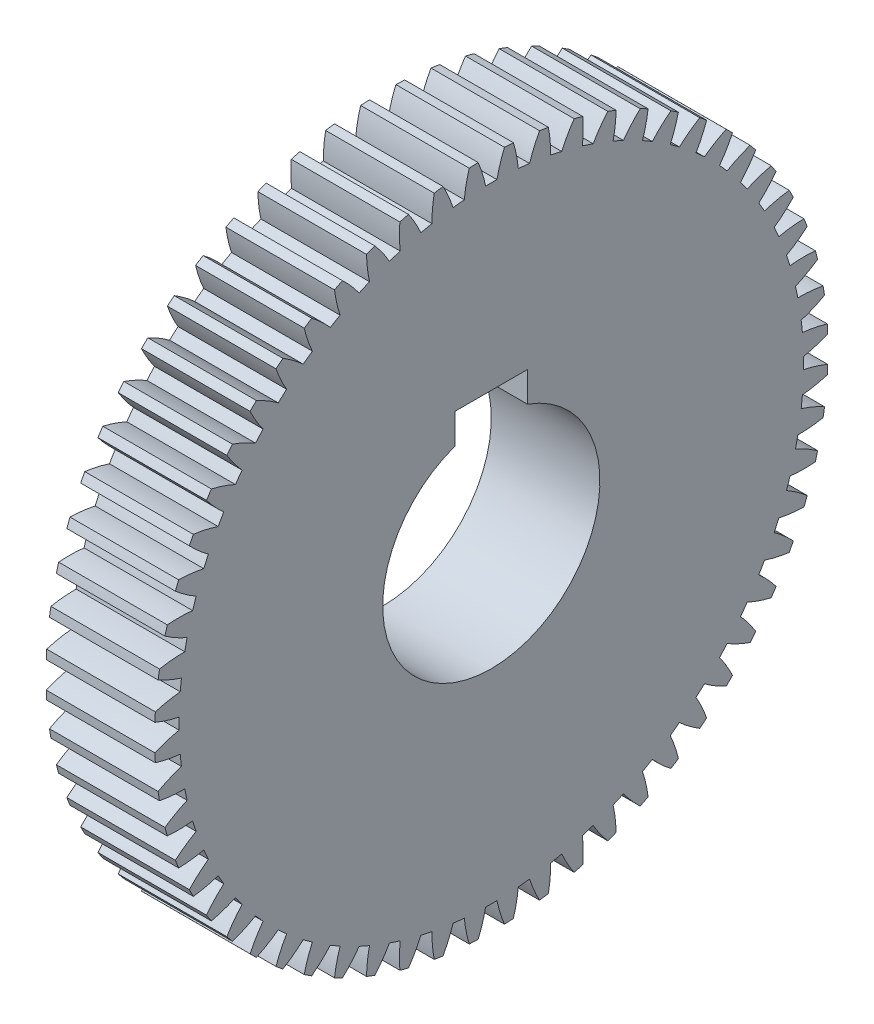
SolidWorks part; units mm, degrees
ref_plane "Plane1" through (0, 0, 0) normal (0, 0, 1) x (1, 0, 0)
ref_plane "Plane2" through (0, 0, 0) normal (0, 1, 0) x (1, 0, 0)
ref_plane "Plane3" through (0, 0, 0) normal (1, 0, 0) x (0, 0, -1)
sketch "HoldingSke" plane through (0, 0, 0) normal (0, 1, 0) x (1, 0, 0)
  line L0 (0, 0) -> (0.3333, -0.5774)
  line L1 (-15, 0) -> (100, 0) construction
  line L2 (0, 0) -> (-2.1039, 2.3779)
  line L3 (0, 0) -> (-11.863, 4.5341)
  line L4 (0, 0) -> (4.318, 7.479)
  line L5 (0, 0) -> (-46.8476, -17.4728)
  line L6 (0, 0) -> (-12.4344, -8.3896)
  line L7 (-2.1039, 2.3779) -> (8.6586, 51.2059)
  line L8 (-76.2, 54.61) -> (-72.9, 54.61)
  line L9 (-67.7845, 28.3722) -> (-49.3413, 33.142)
  line L10 (-76.2, 71.12) -> (104.1128, 71.12)
  line L11 (0, 0) -> (-15, 0)
  line L12 (-76.2, 101.6) -> (-76.147, 101.6)
  line L13 (24.9733, 27.94) -> (52.9518, 28.4284)
  line L14 (24.9733, 27.94) -> (24.9743, 27.94)
  line L15 (24.9733, 27.94) -> (100.4006, 29.5858)
  line L16 (-63.627, -1.5) -> (-12.827, -1.5)
  circle A0 centre (0, 0) radius 15
  circle A1 centre (0, 0) radius 37.5
  circle A2 centre (0, 0) radius 37.5
  circle A3 centre (0, 0) radius 15
  dimension "MHD" = 75
  dimension "Hub_dia" = 75
  dimension "Bore" = 30
  dimension "MBD" = 30
  dimension "Num_teeth" = 60
  dimension "Pitch" = 0.6667
  dimension "Overall_len" = 50
  dimension "Show_teeth" = 60
  dimension "Thickness" = 15
  dimension "OAL" = 50.0001
  dimension "T_dim" = 3.3
  dimension "Ap" = 14.5
  dimension "H" = 19.05
  dimension "Pitch_radius" = 180.3128
  dimension "Width" = 15
  dimension "Backlash" = 0.053
  dimension "Addendum_fac" = 1
  dimension "Dedendum_fac" = 1.25
  dimension "Clearance_fac" = 0.25
  dimension "Dedendum_add" = 0.001
  dimension "Module" = 1.5
sketch "BasProSke" plane through (0, 0, 0) normal (0, 1, 0) x (1, 0, 0)
  line L0 (-10, 0) -> (60, 0) construction
  line L1 (0, 0) -> (0, 46.5)
  line L2 (0, 0) -> (15, 0)
  line L3 (15, 0) -> (15, 46.5)
  line L4 (15, 46.5) -> (0, 46.5)
  dimension "Thickness" = 15
  dimension "Diameter" = 93
revolve "Base-Revolve" add sketch "BasProSke" angle 360 about L0
sketch "TooCutSke" plane through (0, 0, 0) normal (1, 0, 0) x (0, 0, -1)
  line L1 (0, 0) -> (0, 107) construction
  line L2 (0, 0) -> (-1.2707, 44.9821) construction
  line L3 (0, 0) -> (-4.7089, 89.8505) construction
  line L4 (-1.2707, 44.9821) -> (-2.3544, 44.9253) construction
  arc A0 (0.781, 43.1169) -> (-0.781, 43.1169) centre (0, 0) ccw
  arc A1 (1.8295, 46.4894) -> (-1.8295, 46.4894) centre (0, 0) ccw
  circle A2 centre (0, 0) radius 45 construction
  circle A3 centre (0, 0) radius 43.5666 construction
  arc A4 (-0.781, 43.1169) -> (-1.8295, 46.4894) centre (-18.4109, 39.4853) ccw
  arc A5 (1.8295, 46.4894) -> (0.781, 43.1169) centre (18.4109, 39.4853) ccw
  dimension "Root_dia" = 86.248
  dimension "Overcut_dia" = 93.0508
  dimension "Pitch_dia" = 90
  dimension "Base_dia" = 87.1333
  dimension "Flank_rad" = 18
  dimension "Half_ang" = 3
  dimension "Half_CT" = 1.0852
extrude "ToothCut" cut sketch "TooCutSke" along normal through all
fillet "Breaks" [suppressed] radius 0.03
fillet "RootFillets" [suppressed] radius 0.376
pattern_circular "TeethCuts" count 60 every 6 about axis through (-10, 0, 0) along (1, 0, 0) of "ToothCut", "RootFillets", "Breaks"
sketch "HubNeaOneSke" plane through (0, 0, 0) normal (-1, 0, 0) x (0, 0, 1)
  circle A0 centre (0, 0) radius 37.5
  dimension "Diameter" = 75
extrude "HubNearOne" [suppressed] add sketch "HubNeaOneSke" along normal blind 35.0001
sketch "HubNeaBotSke" plane through (0, 0, 0) normal (-1, 0, 0) x (0, 0, 1)
  circle A0 centre (0, 0) radius 37.5
  dimension "Diameter" = 75
extrude "HubNearBoth" [suppressed] add sketch "HubNeaBotSke" along normal blind 17.5
ref_plane "FarPln" through (15, 0, 0) normal (1, 0, 0) x (0, 0, -1)
sketch "HubFarSke" plane through (15, 0, 0) normal (1, 0, 0) x (0, 0, -1)
  circle A0 centre (0, 0) radius 37.5
  dimension "Diameter" = 75
extrude "HubFar" [suppressed] add sketch "HubFarSke" along normal blind 17.5
sketch "BorSke" plane through (0, 0, 0) normal (1, 0, 0) x (0, 0, -1)
  circle A0 centre (0, 0) radius 15
  dimension "Diameter" = 30
extrude "Bore" cut sketch "BorSke" along normal mid plane 100.0001
sketch "KeySke" plane through (0, 0, 0) normal (1, 0, 0) x (0, 0, -1)
  line L0 (-5, 0) -> (-5, 18.3)
  line L1 (-5, 18.3) -> (5, 18.3)
  line L2 (5, 18.3) -> (5, 0)
  line L3 (0, 0) -> (0, 34) construction
  line L4 (-5, 0) -> (5, 0)
  dimension "Offset" = 18.3
  dimension "Width" = 10
extrude "Keyway" cut sketch "KeySke" along normal mid plane 100.0001
pattern_circular "Keyway2" [suppressed] count 2 every 90 about axis through (-10, 0, 0) along (1, 0, 0)
equation "' \"Module@HoldingSke\" = 6.35"
equation "' \"Num_teeth@HoldingSke\" = 12"
equation "' \"Ap@HoldingSke\" =  20"
equation "' \"Ap@HoldingSke\" = 20"
equation "' \"Width@HoldingSke\" = 0.5 * 25.4"
equation "' \"Hub_dia@HoldingSke\"= 1 * 25.4"
equation "' \"Hub_dia@HoldingSke\" = 1 * 25.4"
equation "' \"Overall_len@HoldingSke\" = 1.0 * 25.4"
equation "' \"Bore@HoldingSke\" = 0.75 * 25.4"
equation "' \"T_dim@HoldingSke\" = 0.1 * 25.4"
equation "' \"Width@KeySke\" = 0.25 * 25.4"
equation "' \"Show_teeth@HoldingSke\" = 13"
equation "' \"Backlash@HoldingSke\" = 0.009 * 25.4"
equation "' \"Addendum_fac@HoldingSke\" = 1.0"
equation "' \"Dedendum_fac@HoldingSke\" = 1.25"
equation "' \"Dedendum_add@HoldingSke\" = 0.00005 * 25.4"
equation "' \"Clearance_fac@HoldingSke\" = 0.25"
equation "\"Pitch@HoldingSke\" = 1 / \"Module@HoldingSke\""
equation "\"Overcut_dia@TooCutSke\" = (\"Num_teeth@HoldingSke\" + 2 * \"Addendum_fac@HoldingSke\") / \"Pitch@HoldingSke\" + 0.002 * 25.4"
equation "\"Pitch_dia@TooCutSke\" = \"Num_teeth@HoldingSke\" / \"Pitch@HoldingSke\""
equation "\"Base_dia@TooCutSke\" = \"Num_teeth@HoldingSke\" / \"Pitch@HoldingSke\" * cos((\"Ap@HoldingSke\"  * 3.14159265 / 180))"
equation "\"Root_dia@TooCutSke\" = (\"Num_teeth@HoldingSke\" + 2) / \"Pitch@HoldingSke\" - 2 * (\"Addendum_fac@HoldingSke\" + \"Dedendum_fac@HoldingSke\") / \"Pitch@HoldingSke\" - \"Dedendum_add@HoldingSke\" * 2"
equation "\"Half_ang@TooCutSke\" = 180 / \"Num_teeth@HoldingSke\""
equation "\"Half_CT@TooCutSke\" = \"Num_teeth@HoldingSke\" / \"Pitch@HoldingSke\" * sin((3.14159265 / 2 / \"Num_teeth@HoldingSke\")) / 2 - 7 * \"Backlash@HoldingSke\" / 4"
equation "\"Flank_rad@TooCutSke\" = \"Num_teeth@HoldingSke\" / \"Pitch@HoldingSke\" / 5"
equation "\"Radius@RootFillets\" = \"Clearance_fac@HoldingSke\" / \"Pitch@HoldingSke\" + \"Dedendum_add@HoldingSke\""
equation "\"Break_rad@Breaks\" = 0.02 / \"Pitch@HoldingSke\""
equation "\"Thickness@HoldingSke\" = \"Width@HoldingSke\""
equation "\"OAL@HoldingSke\" = \"Thickness@HoldingSke\""
equation "\"MHD@HoldingSke\" = (\"Num_teeth@HoldingSke\" + 2) / \"Pitch@HoldingSke\" - 2 * (\"Addendum_fac@HoldingSke\" + \"Dedendum_fac@HoldingSke\")  / \"Pitch@HoldingSke\" - \"Dedendum_add@HoldingSke\" * 2"
equation "\"MBD@HoldingSke\" = (\"Num_teeth@HoldingSke\" + 2) / \"Pitch@HoldingSke\" - 2 * (\"Addendum_fac@HoldingSke\" + \"Dedendum_fac@HoldingSke\")  / \"Pitch@HoldingSke\" - \"Dedendum_add@HoldingSke\" * 2 - 0.002 * 25.4"
equation "\"MHD@HoldingSke\" = ((sgn( \"MHD@HoldingSke\" - \"Hub_dia@HoldingSke\" )-1)*( \"MHD@HoldingSke\" - \"Hub_dia@HoldingSke\" ))/-2+ \"Hub_dia@HoldingSke\""
equation "\"MBD@HoldingSke\" = ((sgn( \"MBD@HoldingSke\" - \"Bore@HoldingSke\" )-1)*( \"MBD@HoldingSke\" - \"Bore@HoldingSke\" ))/-2+ \"Bore@HoldingSke\""
equation "\"OAL@HoldingSke\" = ((sgn( \"OAL@HoldingSke\" - \"Overall_len@HoldingSke\" )+1)*( \"OAL@HoldingSke\" - \"Overall_len@HoldingSke\" ))/2 + \"Overall_len@HoldingSke\" + 0.000002 * 25.4"
equation "\"Num_teeth@TeethCuts\" = int( \"Show_teeth@HoldingSke\" ) + 1"
equation "\"Num_teeth@TeethCuts\" = ((sgn( \"Num_teeth@TeethCuts\" - \"Num_teeth@HoldingSke\" )-1)*( \"Num_teeth@TeethCuts\" - \"Num_teeth@HoldingSke\" ))/-2+ \"Num_teeth@HoldingSke\""
equation "\"Num_teeth@TeethCuts\" = ((sgn( \"Num_teeth@TeethCuts\" - 2.0)+1)*( \"Num_teeth@TeethCuts\" - 2.0))/2 +2.0"
equation "\"Angle@TeethCuts\" = 360.0 / \"Num_teeth@HoldingSke\""
equation "\"Diameter@BasProSke\" = (\"Num_teeth@HoldingSke\" + 2 * \"Addendum_fac@HoldingSke\") / \"Pitch@HoldingSke\""
equation "\"Thickness@BasProSke\"  = \"Thickness@HoldingSke\""
equation "' \"Fillet_rad@BasProSke\" =  \"Thickness@HoldingSke\" * 0.05"
equation "' \"Fillet_rad@BasProSke\" = \"Thickness@HoldingSke\" * 0.05"
equation "\"MHD@HoldingSke\" = ((sgn( \"MHD@HoldingSke\" - \"Root_dia@TooCutSke\" )-1)*( \"MHD@HoldingSke\" - \"Root_dia@TooCutSke\" ))/-2+ \"Root_dia@TooCutSke\""
equation "\"Diameter@HubNeaOneSke\" = \"MHD@HoldingSke\""
equation "\"Length@HubNearOne\" = \"OAL@HoldingSke\" - \"Thickness@BasProSke\""
equation "\"Diameter@HubNeaBotSke\" = \"MHD@HoldingSke\""
equation "\"Length@HubNearBoth\" = ( \"OAL@HoldingSke\" - \"Thickness@BasProSke\" ) / 2.0"
equation "\"Thickness@FarPln\" = \"Thickness@BasProSke\""
equation "\"Diameter@HubFarSke\" = \"MHD@HoldingSke\""
equation "\"Length@HubFar\" = ( \"OAL@HoldingSke\" - \"Thickness@BasProSke\" ) / 2.0"
equation "\"Diameter@BorSke\" = \"MBD@HoldingSke\""
equation "\"D1@Bore\" = \"OAL@HoldingSke\" * 2.0"
equation "\"D1@Keyway\" = \"OAL@HoldingSke\" * 2.0"
equation "\"Offset@KeySke\" = \"T_dim@HoldingSke\" + \"MBD@HoldingSke\" / 2.0"
